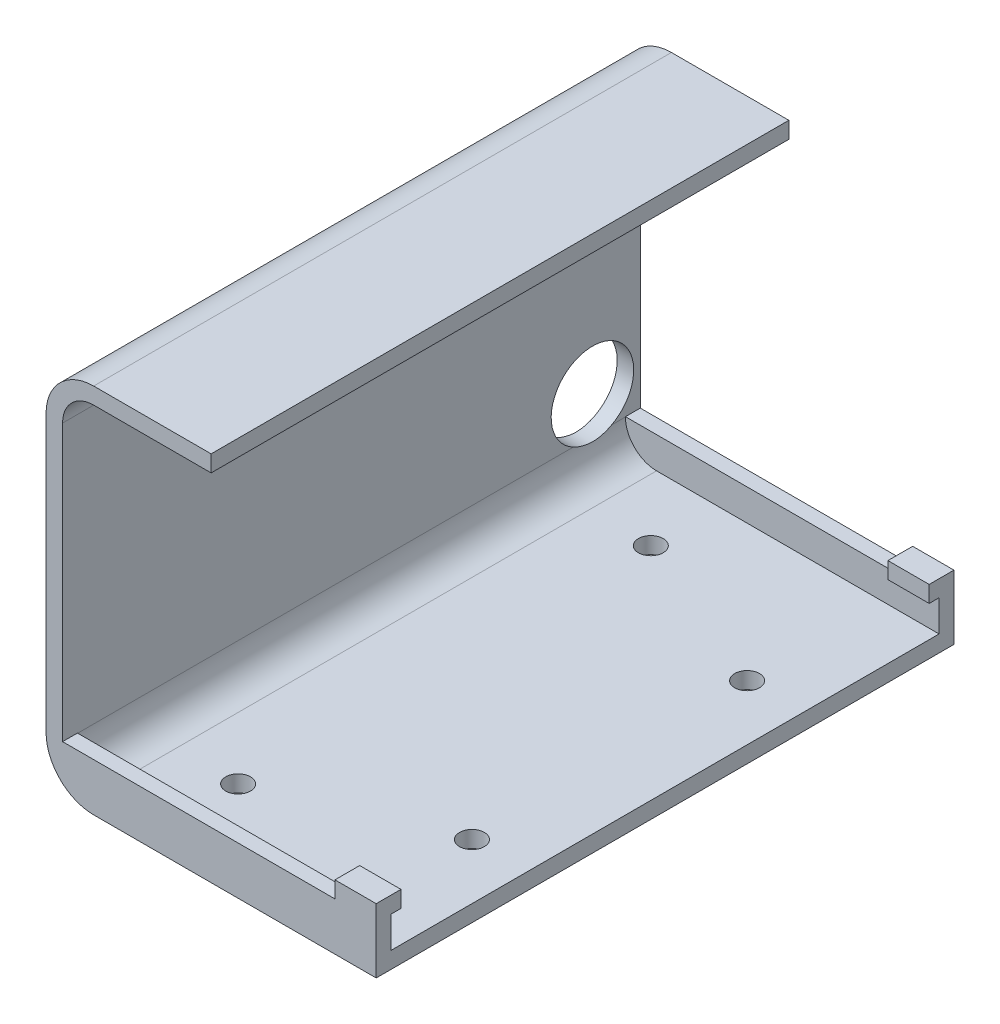
SolidWorks part; units mm, degrees
material "ABS"
ref_plane "Front Plane" through (0, 0, 0) normal (0, 0, 1) x (1, 0, 0)
ref_plane "Top Plane" through (0, 0, 0) normal (0, 1, 0) x (1, 0, 0)
ref_plane "Right Plane" through (0, 0, 0) normal (1, 0, 0) x (0, 0, -1)
sketch "Sketch1" plane through (0, 0, 0) normal (0, 0, 1) x (1, 0, 0)
  line L0 (-30.3982, 19.9644) -> (-30.3982, -13.4956)
  line L1 (-24.6282, -19.2656) -> (9.6018, -19.2656)
  line L7 (-10.3982, 25.7344) -> (-24.6282, 25.7344)
  line L8 (-10.3982, 23.7344) -> (-24.6282, 23.7344)
  line L9 (-28.3982, 19.9644) -> (-28.3982, -13.4956)
  line L10 (-24.6282, -17.2656) -> (9.6018, -17.2656)
  line L11 (-10.3982, 25.7344) -> (-10.3982, 23.7344)
  line L12 (9.6018, -19.2656) -> (9.6018, -17.2656)
  arc A0 (-30.3982, 19.9644) -> (-24.6282, 25.7344) centre (-24.6282, 19.9644) cw
  arc A1 (-30.3982, -13.4956) -> (-24.6282, -19.2656) centre (-24.6282, -13.4956) ccw
  arc A2 (-28.3982, 19.9644) -> (-24.6282, 23.7344) centre (-24.6282, 19.9644) cw
  arc A3 (-28.3982, -13.4956) -> (-24.6282, -17.2656) centre (-24.6282, -13.4956) ccw
  point P5 (-30.3982, 25.7344)
  point P9 (-30.3982, -19.2656)
  dimension "D4" = 5.77
  dimension "D1" = 45
  dimension "D2" = 20
  dimension "D3" = 40
  dimension "D5" = 2
extrude "Boss-Extrude1" add sketch "Sketch1" along normal blind 70
sketch "Sketch2" plane through (0, -17.2656, 0) normal (0, 1, 0) x (1, 0, 0)
  line L0 (-30.3982, -35) -> (48.3397, -35) construction
  line L1 (-10.0418, -1.8) -> (17.0103, -1.8)
  line L2 (-10.0418, -1.8) -> (-10.0418, -68.2)
  line L3 (-10.0418, -68.2) -> (17.0103, -68.2)
  line L4 (17.0103, -1.8) -> (17.0103, -68.2)
  line L5 (-30.3982, -70) -> (-30.3982, 0) construction
  point P8 (17.0103, -35)
  dimension "D1" = 66.4
sketch "Sketch3" plane through (9.6018, 0, 0) normal (1, 0, 0) x (0, 0, -1)
  line L0 (-35, -17.2656) -> (-35, -19.2656) construction
  line L1 (-70, -17.2656) -> (-68.2, -17.2656)
  line L2 (-70, -17.2656) -> (-70, -13.4656)
  line L3 (-70, -13.4656) -> (-68.2, -13.4656)
  line L4 (-68.2, -17.2656) -> (-68.2, -13.4656)
  line L5 (-1.8, -17.2656) -> (-68.2, -17.2656) construction
  line L6 (-70, -19.2656) -> (0, -19.2656) construction
  line L7 (0, -13.4656) -> (-1.8, -13.4656)
  line L8 (-1.8, -17.2656) -> (-1.8, -13.4656)
  line L9 (0, -17.2656) -> (-1.8, -17.2656)
  line L10 (0, -17.2656) -> (0, -13.4656)
  dimension "D1" = 3.8
extrude "Boss-Extrude3" add sketch "Sketch3" against normal up to next
sketch "Sketch4" plane through (0, -13.4656, 0) normal (0, 1, 0) x (1, 0, 0)
  line L1 (9.6018, -70) -> (4.6018, -70)
  line L2 (9.6018, -70) -> (9.6018, -67)
  line L3 (9.6018, -67) -> (4.6018, -67)
  line L4 (4.6018, -70) -> (4.6018, -67)
  line L5 (9.6018, 0) -> (4.6018, 0)
  line L6 (9.6018, 0) -> (9.6018, -3)
  line L7 (9.6018, -3) -> (4.6018, -3)
  line L8 (4.6018, 0) -> (4.6018, -3)
  dimension "D1" = 3
  dimension "D2" = 5
extrude "Boss-Extrude4" add sketch "Sketch4" along normal blind 2
sketch "Sketch5" plane through (0, -19.2656, 0) normal (0, -1, 0) x (-1, 0, 0)
  line L0 (24.6282, -70) -> (24.6282, 0) construction
  line L1 (30.3982, -35) -> (-48.3397, -35) construction
  line L2 (-9.6018, -35) -> (24.6142, -35) construction
  line L3 (-9.6018, -70) -> (-9.6018, 0) construction
  circle A0 centre (17.1282, -60) radius 1.5
  circle A1 centre (17.1282, -10) radius 1.5
  circle A2 centre (-2.8718, -51.67) radius 1.5
  circle A3 centre (-2.8718, -18.33) radius 1.5
  dimension "D3" = 3
  dimension "D1" = 7.5
  dimension "D2" = 25
  dimension "D4" = 8.33
  dimension "D5" = 20
extrude "Cut-Extrude1" cut sketch "Sketch5" against normal up to next
sketch "Sketch6" plane through (-30.3982, 0, 0) normal (-1, 0, 0) x (0, 0, 1)
  line L0 (0, 19.9644) -> (0, -13.4956) construction
  line L1 (68.2, -17.2656) -> (1.8, -17.2656) construction
  circle A0 centre (5.8, -9.0656) radius 5
  dimension "D2" = 10
  dimension "D1" = 5.8
  dimension "D3" = 8.2
extrude "Cut-Extrude2" cut sketch "Sketch6" against normal up to next
